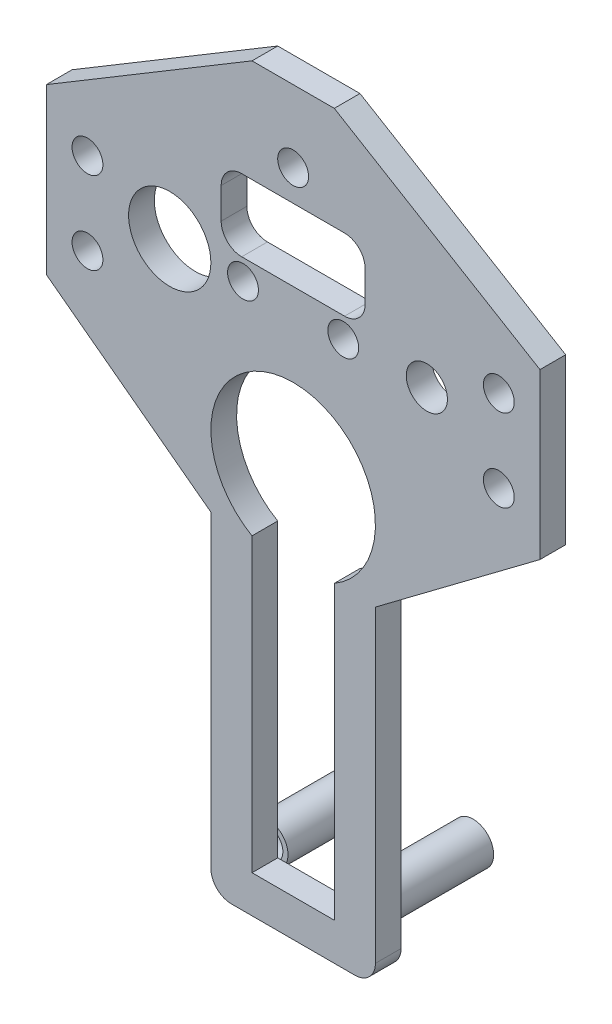
SolidWorks part; units mm, degrees
ref_plane "Front Plane" through (0, 0, 0) normal (0, 0, 1) x (1, 0, 0)
ref_plane "Top Plane" through (0, 0, 0) normal (0, 1, 0) x (1, 0, 0)
ref_plane "Right Plane" through (0, 0, 0) normal (1, 0, 0) x (0, 0, -1)
sketch "Sketch1" plane through (0, 0, 0) normal (0, 0, 1) x (1, 0, 0)
  line L0 (-24, 5.0718) -> (-24, 21.0718)
  line L1 (-24, 21.0718) -> (-4, 33.0718)
  line L2 (-4, 33.0718) -> (4, 33.0718)
  line L3 (4, 33.0718) -> (24, 21.0718)
  line L4 (24, 21.0718) -> (24, 5.0718)
  line L5 (24, 5.0718) -> (8, -6.9282)
  line L6 (8, -6.9282) -> (8, -38.9282)
  line L7 (-8, -38.9282) -> (8, -38.9282)
  line L8 (-8, -38.9282) -> (-8, -6.9282)
  line L9 (-8, -6.9282) -> (-24, 5.0718)
  line L10 (-4, -35.2982) -> (4, -35.2982)
  line L11 (-4, -35.2982) -> (-4, -6.9282)
  line L12 (4, -6.9282) -> (4, -35.2982)
  line L13 (-5, 23.0718) -> (5, 23.0718)
  line L14 (7, 21.0718) -> (7, 18.0718)
  line L15 (-7, 21.0718) -> (-7, 18.0718)
  line L16 (-5, 16.0718) -> (5, 16.0718)
  arc A0 (-4, -6.9282) -> (4, -6.9282) centre (0, 0) cw
  arc A1 (5, 23.0718) -> (7, 21.0718) centre (5, 21.0718) cw
  arc A2 (-5, 23.0718) -> (-7, 21.0718) centre (-5, 21.0718) ccw
  arc A3 (-7, 18.0718) -> (-5, 16.0718) centre (-5, 18.0718) ccw
  arc A4 (5, 16.0718) -> (7, 18.0718) centre (5, 18.0718) ccw
  circle A5 centre (-12, 14.0718) radius 4
  circle A6 centre (-4.875, 14.0718) radius 1.5
  circle A7 centre (4.875, 14.0718) radius 1.5
  circle A8 centre (0, 26.0718) radius 1.5
  circle A9 centre (20, 17.0718) radius 1.5
  circle A10 centre (20, 9.0718) radius 1.5
  circle A11 centre (-20, 17.0718) radius 1.5
  circle A12 centre (-20, 9.0718) radius 1.5
  circle A13 centre (13, 14.0718) radius 2
  dimension "D2" = 3
  dimension "D4" = 32
  dimension "D5" = 10
  dimension "D6" = 28.37
  dimension "D15" = 48
  dimension "D34" = 24
extrude "Boss-Extrude1" add sketch "Sketch1" along normal blind 2.5
sketch "Sketch2" plane through (0, 0, 0) normal (0, 0, -1) x (-1, 0, 0)
  line L0 (-5, -32.1616) -> (5, -32.1616) construction
  line L1 (0, -32.1616) -> (0, -34.5316) construction
  circle A3 centre (-5, -34.5316) radius 2
  circle A4 centre (-5, -34.5316) radius 1.5
  circle A5 centre (5, -34.5316) radius 1.5
  circle A6 centre (5, -34.5316) radius 2
  dimension "D1" = 2.37
  dimension "D2" = 4
  dimension "D3" = 3
extrude "Boss-Extrude2" add sketch "Sketch2" along normal blind 10
fillet "Fillet1" radius 2 2 edges at (8, -38.9282, 1.25) (-8, -38.9282, 1.25)
